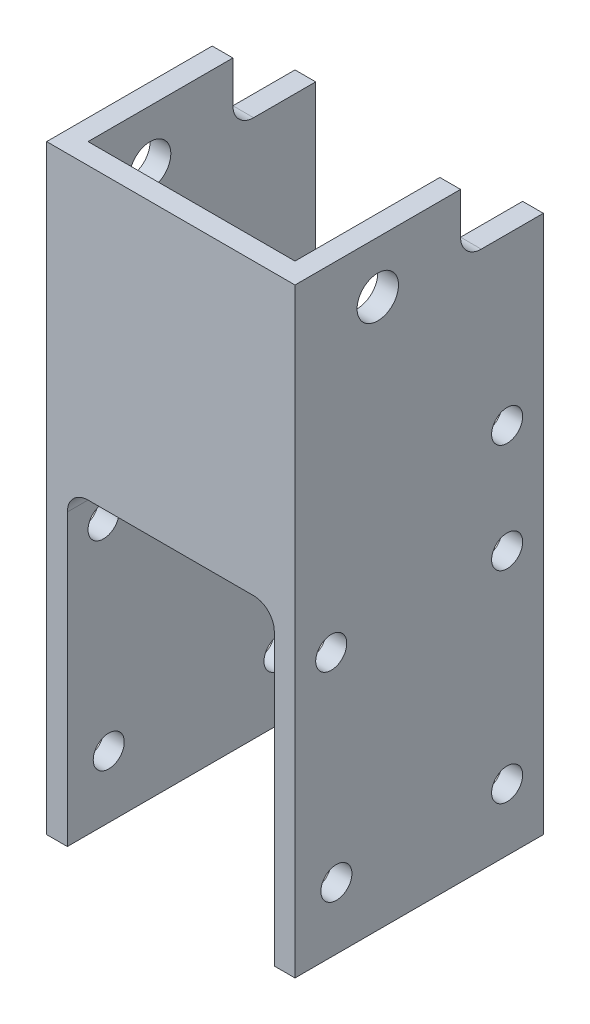
SolidWorks part; units mm, degrees
material "6061-T6 (SS)"
ref_plane "Front" through (0, 0, 0) normal (0, 0, 1) x (1, 0, 0)
ref_plane "Top" through (0, 0, 0) normal (0, 1, 0) x (1, 0, 0)
ref_plane "Right" through (0, 0, 0) normal (1, 0, 0) x (0, 0, -1)
sketch "Sketch1" plane through (0, 0, 0) normal (0, 1, 0) x (1, 0, 0)
  line L0 (-38.1, 76.2) -> (-38.1, 0)
  line L1 (-50, 0) -> (50, 0) construction
  line L2 (-38.1, 0) -> (0, 0)
  line L3 (0, 0) -> (38.1, 0)
  line L4 (38.1, 0) -> (38.1, 76.2)
  line L5 (38.1, 76.2) -> (31.75, 76.2)
  line L6 (31.75, 76.2) -> (31.75, 6.35)
  line L7 (31.75, 6.35) -> (-31.75, 6.35)
  line L8 (-31.75, 6.35) -> (-31.75, 76.2)
  line L9 (-31.75, 76.2) -> (-38.1, 76.2)
  line L10 (31.75, 6.35) -> (31.75, 0) construction
  dimension "D1" = 6.35
  dimension "D2" = 76.2
  dimension "D3" = 63.5
  dimension "D4" = 76.2
extrude "Boss-Extrude1" add sketch "Sketch1" along normal blind 184.15
sketch "Sketch2" plane through (0, 0, -6.35) normal (0, 0, -1) x (-1, 0, 0)
  line L0 (-31.75, 184.15) -> (-31.75, 0) construction
  line L1 (31.75, 0) -> (-31.75, 0)
  line L2 (31.75, 0) -> (31.75, 95.25)
  line L3 (31.75, 95.25) -> (-31.75, 95.25)
  line L4 (-31.75, 0) -> (-31.75, 95.25)
  dimension "D1" = 95.25
extrude "Cut-Extrude1" cut sketch "Sketch2" against normal through all
sketch "Sketch3" plane through (38.1, 0, 0) normal (1, 0, 0) x (0, 0, -1)
  line L0 (0, 19.05) -> (65.0875, 19.05) construction
  line L1 (0, 184.15) -> (0, 0) construction
  line L2 (0, 0) -> (76.2, 0) construction
  line L3 (65.0875, 19.05) -> (65.0875, 80.9752) construction
  line L4 (65.0875, 80.9752) -> (11.1125, 80.9752) construction
  line L5 (65.0875, 80.9752) -> (65.0875, 114.3) construction
  line L6 (76.2, 184.15) -> (76.2, 0) construction
  point P6 (12.7, 19.05)
  dimension "D1" = 19.05
  dimension "D2" = 65.0875
  dimension "D3" = 12.7
  dimension "D4" = 61.9252
  dimension "D5" = 95.25
  dimension "D6" = 11.1125
hole_wizard "3/8 (0.375) Clearance Dowel Hole1" positions "Sketch5" profile "Sketch4" hole size "3/8" standard "ANSI Inch" end condition through all
sketch "Sketch5" plane through (38.1, 0, 0) normal (1, 0, 0) x (0, 0, -1)
  point P0 (65.0875, 19.05)
  point P4 (12.7, 19.05)
  point P7 (65.0875, 114.3)
sketch "Sketch4" plane through (38.1, 19.05, -65.0875) normal (0, 1, 0) x (0, 0, -1)
  line L0 (0, 0) -> (0, 76.2)
  line L1 (0, 76.2) -> (4.7625, 76.2)
  line L2 (4.7625, 76.2) -> (4.7625, 0)
  line L5 (4.7625, 0) -> (0, 0)
  line L11 (0, -6.35) -> (0, 107.95) construction
  dimension "Thru Hole Dia." = 9.525
  dimension "Thru Hole Depth" = 76.2
sketch "Sketch6" plane through (38.1, 0, 0) normal (1, 0, 0) x (0, 0, -1)
  line L2 (76.2, 184.15) -> (50.8, 184.15)
  line L4 (76.2, 184.15) -> (76.2, 165.1)
  line L5 (76.2, 165.1) -> (50.8, 165.1)
  line L6 (50.8, 184.15) -> (50.8, 165.1)
  dimension "D1" = 19.05
  dimension "D2" = 25.4
extrude "Cut-Extrude2" cut sketch "Sketch6" against normal through all
sketch "Sketch7" plane through (38.1, 0, 0) normal (1, 0, 0) x (0, 0, -1)
  line L0 (25.4, 184.15) -> (25.4, 168.275) construction
  line L1 (0, 184.15) -> (50.8, 184.15) construction
  line L2 (25.4, 168.275) -> (0, 168.275) construction
  line L3 (0, 184.15) -> (0, 0) construction
  dimension "D1" = 15.875
  dimension "D2" = 25.4
hole_wizard "1/2 (0.5) Diameter Hole1" positions "Sketch10" profile "Sketch9" hole size "1/2" standard "ANSI Inch" end condition through all
sketch "Sketch10" plane through (38.1, 0, 0) normal (1, 0, 0) x (0, 0, -1)
  point P0 (25.4, 168.275)
sketch "Sketch9" plane through (38.1, 168.275, -25.4) normal (0, 1, 0) x (0, 0, -1)
  line L0 (0, 0) -> (0, 76.2)
  line L1 (0, 76.2) -> (6.35, 76.2)
  line L2 (6.35, 76.2) -> (6.35, 0)
  line L5 (6.35, 0) -> (0, 0)
  line L11 (0, -6.35) -> (0, 107.95) construction
  dimension "Thru Hole Dia." = 12.7
  dimension "Thru Hole Depth" = 76.2
fillet "Fillet1" radius 6.35 4 edges at (-34.925, 165.1, -50.8) (34.925, 165.1, -50.8) (-31.75, 95.25, -3.175) (31.75, 95.25, -3.175)
hole_wizard "3/8 (0.375) Clamp Adjust Hole" positions "Sketch12" profile "Sketch11" hole size "3/8" standard "ANSI Inch"
sketch "Sketch12" plane through (38.1, 0, 0) normal (1, 0, 0) x (0, 0, -1)
  point P3 (11.1125, 80.9752)
  point P6 (65.0875, 80.9752)
sketch "Sketch11" plane through (38.1, 80.9752, -11.1125) normal (0, 1, 0) x (0, 0, -1)
  line L0 (0, 0) -> (0, 85.4116)
  line L1 (0, 85.4116) -> (4.7625, 82.55)
  line L2 (4.7625, 82.55) -> (4.7625, 0)
  line L5 (4.7625, 0) -> (0, 0)
  line L10 (0, 85.4116) -> (-4.7625, 82.55) construction
  line L11 (0, -6.35) -> (0, 107.95) construction
  dimension "Hole Dia." = 9.525
  dimension "Hole Depth" = 82.55
  dimension "Drill Angle" = 118
sketch "Sketch13" plane through (38.1, 0, 0) normal (1, 0, 0) x (0, 0, -1)
  line L1 (25.2775, 161.9262) -> (19.05, 161.9262)
  line L2 (25.2775, 161.9262) -> (25.2775, 168.275)
  line L3 (25.2775, 168.275) -> (19.05, 168.275)
  line L4 (19.05, 161.9262) -> (19.05, 168.275)
  circle A0 centre (25.4, 168.275) radius 6.35 construction
extrude "Boss-Extrude3" [suppressed] add sketch "Sketch13" against normal blind 6.35
mirror "Mirror3" [suppressed] about plane through (0, 0, 0) normal (1, 0, 0)
